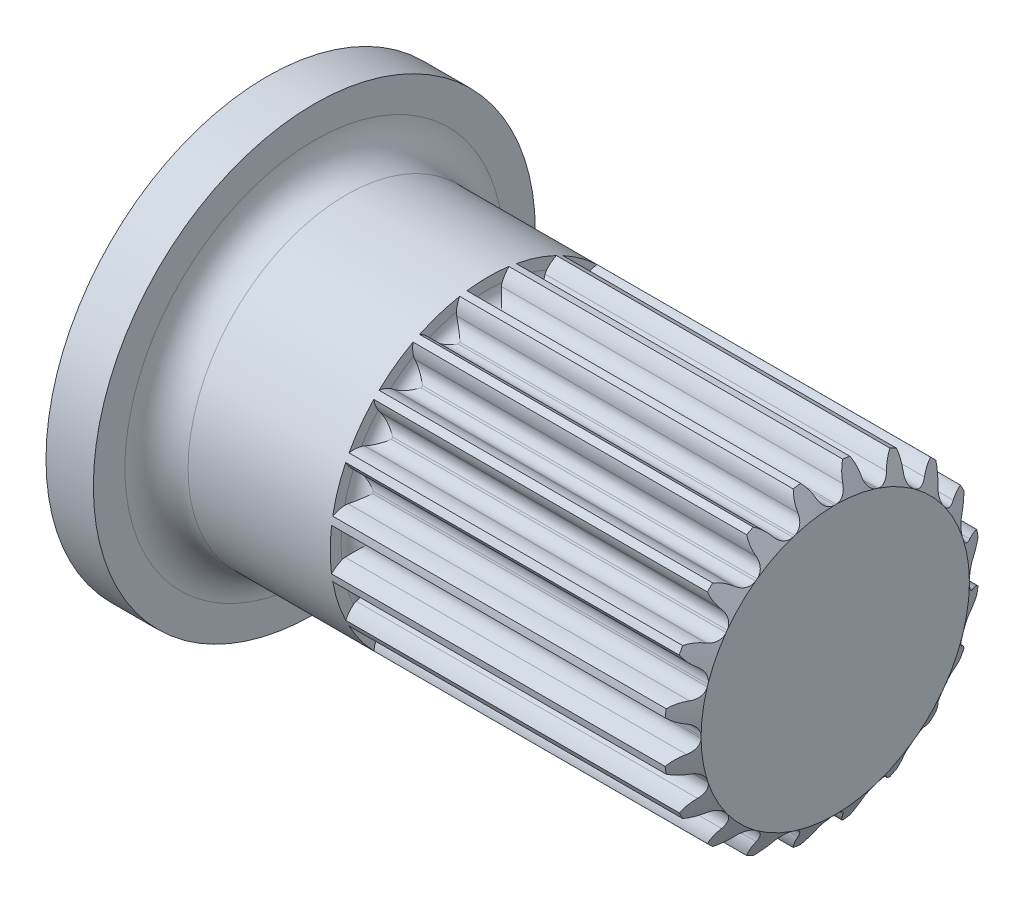
SolidWorks part; units mm, degrees
ref_plane "Front Plane" through (0, 0, 0) normal (0, 0, 1) x (1, 0, 0)
ref_plane "Top Plane" through (0, 0, 0) normal (0, 1, 0) x (1, 0, 0)
ref_plane "Right Plane" through (0, 0, 0) normal (1, 0, 0) x (0, 0, -1)
sketch "Sketch1" plane through (0, 0, 0) normal (0, 0, 1) x (1, 0, 0)
  line L0 (36, 0) -> (0, 0)
  line L10 (0, 14) -> (3, 14)
  line L11 (3, 14) -> (3, 10)
  line L12 (3, 10) -> (36, 10)
  line L17 (36, 10) -> (36, 0)
  line L18 (0, 14) -> (0, 0)
  dimension "D13" = 3
  dimension "D12" = 14
  dimension "D10" = 10
  dimension "D2" = 36
revolve "Revolve1" add sketch "Sketch1" angle 360 about L0
fillet "Fillet1" radius 2 1 edges at (3, 10, 0)
sketch "Sketch2" plane through (36, 0, 0) normal (1, 0, 0) x (0, 0, -1)
  line L0 (0, 0) -> (0, 10) construction
  arc A1 (-0.75, 8.4668) -> (-1.3322, 9.9109) centre (-2.7497, 8.5) ccw
  arc A2 (1.3322, 9.9109) -> (0.75, 8.4668) centre (2.7497, 8.5) ccw
  circle A3 centre (0, 0) radius 10 construction
  arc A4 (1.3322, 9.9109) -> (-1.3322, 9.9109) centre (0, 0) ccw
  arc A5 (-0.75, 8.4668) -> (0.75, 8.4668) centre (0, 0) cw
  dimension "D1" = 4
  dimension "D3" = 8.5
  dimension "D2" = 8.5
  dimension "D4" = 1.5
extrude "Cut-Extrude2" cut sketch "Sketch2" against normal blind 22
fillet "Fillet2" radius 0.8 3 edges at (25, 8.4668, -0.75) (25, 8.4668, 0.75) (14, 8.5, 0)
pattern_circular "CirPattern1" count 20 over 360 about axis through (0, 0, 0) along (1, 0, 0) of "Cut-Extrude2", "Fillet2"
sketch "Sketch3" plane through (36, 0, 0) normal (1, 0, 0) x (0, 0, -1)
  circle A0 centre (0, 0) radius 8.5
  dimension "D1" = 17
extrude "Cut-Extrude3" cut sketch "Sketch3" against normal blind 1 draft 60 flip side to cut
equation "\"A\"= 12mm"
equation "\"D13@Sketch1\"=\"A\"*(3/12)"
equation "\"D12@Sketch1\"=\"A\"*(14/12)"
equation "\"D10@Sketch1\"=\"A\"*(10/12)"
equation "\"D2@Sketch1\"=\"A\"*(36/12)"
equation "\"D1@Fillet1\"=\"A\"*(2/12)"
equation "\"D1@Sketch2\"=\"A\"*(4/12)"
equation "\"D2@Sketch2\"=\"A\"*(8.5/12)"
equation "\"D3@Sketch2\"=\"A\"*(8.5/12)"
equation "\"D4@Sketch2\"=\"A\"*(1.5/12)"
equation "\"D1@Cut-Extrude2\"=\"A\"*(22/12)"
equation "\"D1@Fillet2\"=\"A\"*(0.8/12)"
equation "\"D1@Sketch3\"=\"A\"*(17/12)"
equation "\"D1@Cut-Extrude3\"=\"A\"*(1/12)"
